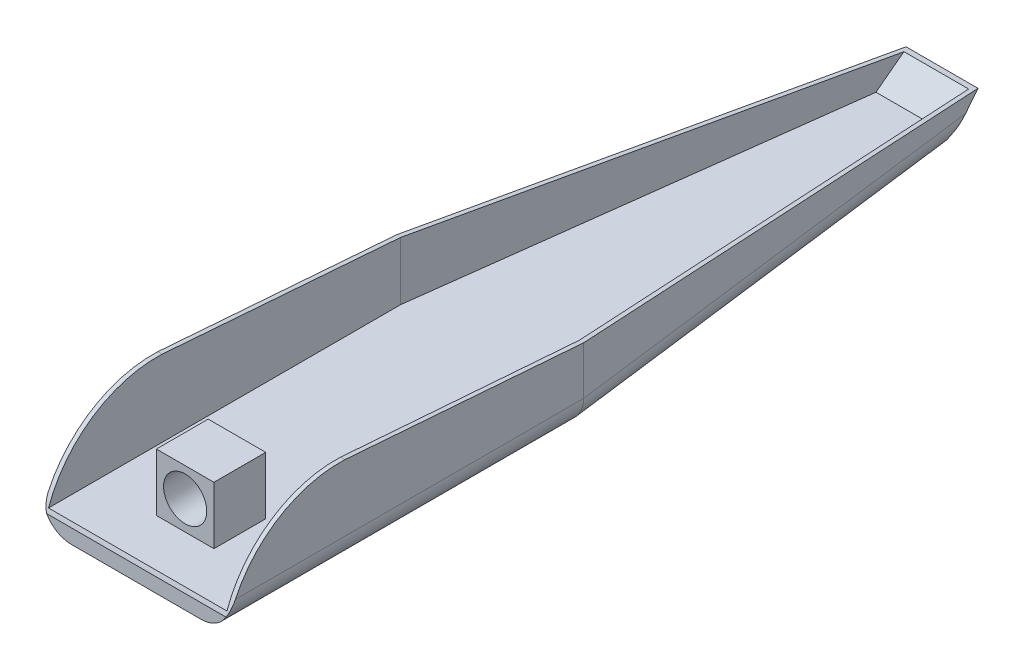
SolidWorks part; units mm, degrees
ref_plane "Front Plane" through (0, 0, 0) normal (0, 0, 1) x (1, 0, 0)
ref_plane "Top Plane" through (0, 0, 0) normal (0, 1, 0) x (1, 0, 0)
ref_plane "Right Plane" through (0, 0, 0) normal (1, 0, 0) x (0, 0, -1)
sketch "Sketch1" plane through (0, 0, 0) normal (1, 0, 0) x (0, 0, -1)
  line L0 (-106.3577, 0) -> (163.6423, 0)
  line L1 (163.6423, 0) -> (173.6423, 9.798)
  line L2 (173.6423, 9.798) -> (-66.3577, 28.0501)
  arc A0 (-106.3577, 0) -> (-66.3577, 28.0501) centre (-68.1715, -11.9088) cw
  dimension "D4" = 40
  dimension "D1" = 270
  dimension "D2" = 280
  dimension "D3" = 14
  dimension "D5" = 240
  dimension "D6" = 28.0501
extrude "Boss-Extrude1" add sketch "Sketch1" along normal blind 65
sketch "Sketch3" plane through (0, 0, 0) normal (0, -1, 0) x (1, 0, 0)
  line L0 (0, -16.6423) -> (20, -173.6423)
  line L2 (0, 106.3577) -> (0, -163.6423) construction
  line L5 (65, 106.3577) -> (0, 106.3577) construction
  line L6 (65, -173.6423) -> (0, -173.6423) construction
  dimension "D1" = 123
  dimension "D2" = 20
sketch "Sketch4" plane through (0, 0, 0) normal (0, -1, 0) x (-1, 0, 0)
  line L0 (-32.5, -106.3577) -> (-32.5, 183.2481) construction
  line L1 (-65, -106.3577) -> (0, -106.3577) construction
sketch "Sketch5" plane through (0, 0, 0) normal (0, -1, 0) x (1, 0, 0)
  line L0 (65, -16.6423) -> (45, -173.6423)
  line L1 (65, 106.3577) -> (65, -163.6423) construction
  line L2 (65, -173.6423) -> (0, -173.6423) construction
  dimension "D1" = 20
  dimension "D2" = 123
extrude "Cut-Extrude1" cut sketch "Sketch3" against normal through all and the other way through all flip side to cut contours L0
extrude "Cut-Extrude2" cut sketch "Sketch5" against normal through all and the other way through all contours L0
shell "Shell2" thickness 1.5
sketch "Sketch7" plane through (0, 1.5, 0) normal (0, 1, 0) x (1, 0, 0)
  line L1 (22.5, -71.365) -> (42.5, -71.365)
  line L2 (22.5, -71.365) -> (22.5, -89.365)
  line L3 (22.5, -89.365) -> (42.5, -89.365)
  line L4 (42.5, -71.365) -> (42.5, -89.365)
  line L5 (22.5, -71.365) -> (42.5, -89.365) construction
  line L6 (22.5, -89.365) -> (42.5, -71.365) construction
  line L8 (32.5, -106.3577) -> (32.5, 183.2481) construction
  point P0 (32.5, -80.365)
  dimension "D1" = 20
  dimension "D3" = 18
extrude "Boss-Extrude2" add sketch "Sketch7" along normal blind 20
sketch "Sketch8" plane through (0, 0, 89.365) normal (0, 0, 1) x (1, 0, 0)
  line L0 (42.5, 21.5) -> (42.5, 1.5) construction
  line L1 (22.5, 21.5) -> (42.5, 21.5) construction
  circle A0 centre (32.5, 11.5) radius 7.5
  point P4 (32.5, 21.5)
  dimension "D1" = 15
  dimension "D2" = 10
  dimension "D3" = 10
extrude "Cut-Extrude3" cut sketch "Sketch8" against normal blind 20 contours A0
sketch "Sketch18" plane through (0, 0, 0) normal (0, -1, 0) x (1, 0, 0)
  line L0 (65, 106.3577) -> (0, 106.3577) construction
  line L1 (65, 106.3577) -> (65, -16.6423) construction
  line L2 (65, -16.6423) -> (46.2739, -163.6423) construction
  line L3 (46.2739, -163.6423) -> (18.7261, -163.6423) construction
  line L4 (0, -16.6423) -> (18.7261, -163.6423) construction
  line L5 (0, 106.3577) -> (0, -16.6423) construction
  line L6 (65, 106.3577) -> (0, 106.3577)
  line L7 (65, 106.3577) -> (65, -16.6423)
  line L8 (65, -16.6423) -> (46.2739, -163.6423)
  line L9 (46.2739, -163.6423) -> (18.7261, -163.6423)
  line L10 (0, -16.6423) -> (18.7261, -163.6423)
  line L11 (0, 106.3577) -> (0, -16.6423)
extrude "Boss-Extrude4" add sketch "Sketch18" along normal blind 5
fillet "Fillet12" radius 10 4 edges at (65, -5, 44.8577) (0, -5, 44.8577) (9.3631, -5, -90.1423) (55.6369, -5, -90.1423)
